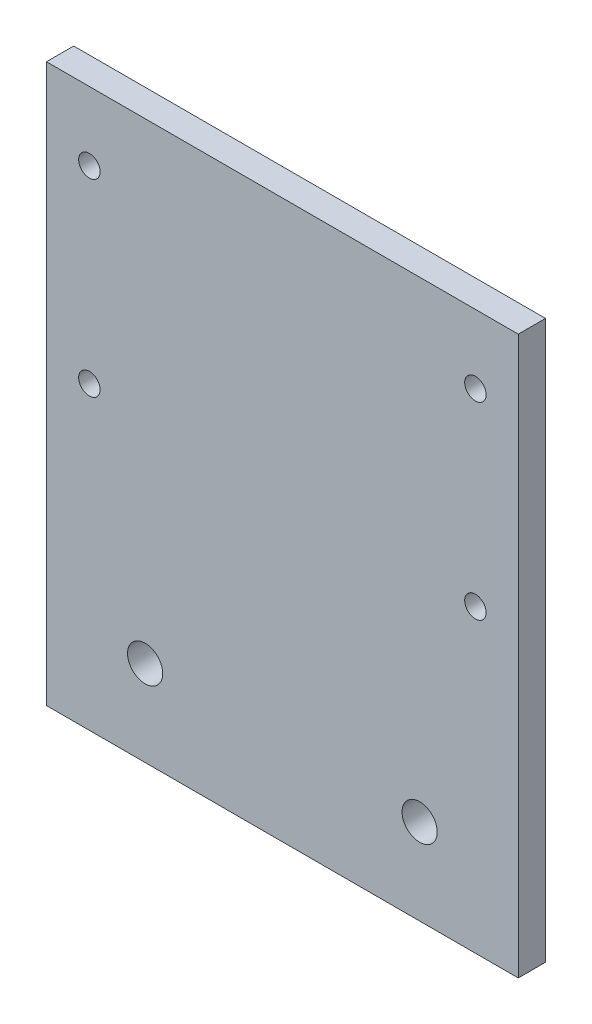
SolidWorks part; units mm, degrees
ref_plane "Front Plane" through (0, 0, 0) normal (0, 0, 1) x (1, 0, 0)
ref_plane "Top Plane" through (0, 0, 0) normal (0, 1, 0) x (1, 0, 0)
ref_plane "Right Plane" through (0, 0, 0) normal (1, 0, 0) x (0, 0, -1)
sketch "Sketch1" plane through (0, 0, 0) normal (0, 0, 1) x (1, 0, 0)
  line L0 (27.5, 65) -> (27.5, 0) construction
  line L1 (0, 0) -> (55, 0)
  line L2 (0, 0) -> (0, 65)
  line L3 (0, 65) -> (55, 65)
  line L4 (55, 0) -> (55, 65)
  line L5 (5, 57) -> (50, 57) construction
  line L6 (5, 57) -> (5, 35) construction
  line L7 (5, 35) -> (50, 35) construction
  line L8 (50, 57) -> (50, 35) construction
  line L9 (11.5, 10) -> (43.5, 10) construction
  circle A0 centre (5, 57) radius 1.25
  circle A1 centre (50, 57) radius 1.25
  circle A2 centre (50, 35) radius 1.25
  circle A3 centre (5, 35) radius 1.25
  circle A4 centre (11.5, 10) radius 2.05
  circle A5 centre (43.5, 10) radius 2.05
  point P11 (27.5, 57)
  point P23 (27.5, 10)
  point P24 (0, 0)
  dimension "D6" = 2.5
  dimension "D9" = 4.1
  dimension "D10" = 4.1
  dimension "D1" = 55
  dimension "D2" = 65
  dimension "D3" = 45
  dimension "D4" = 22
  dimension "D5" = 35
  dimension "D11" = 32
  dimension "D12" = 20
  dimension "D7" = 2
  dimension "D8" = 2
extrude "Boss-Extrude1" add sketch "Sketch1" along normal blind 3.175
